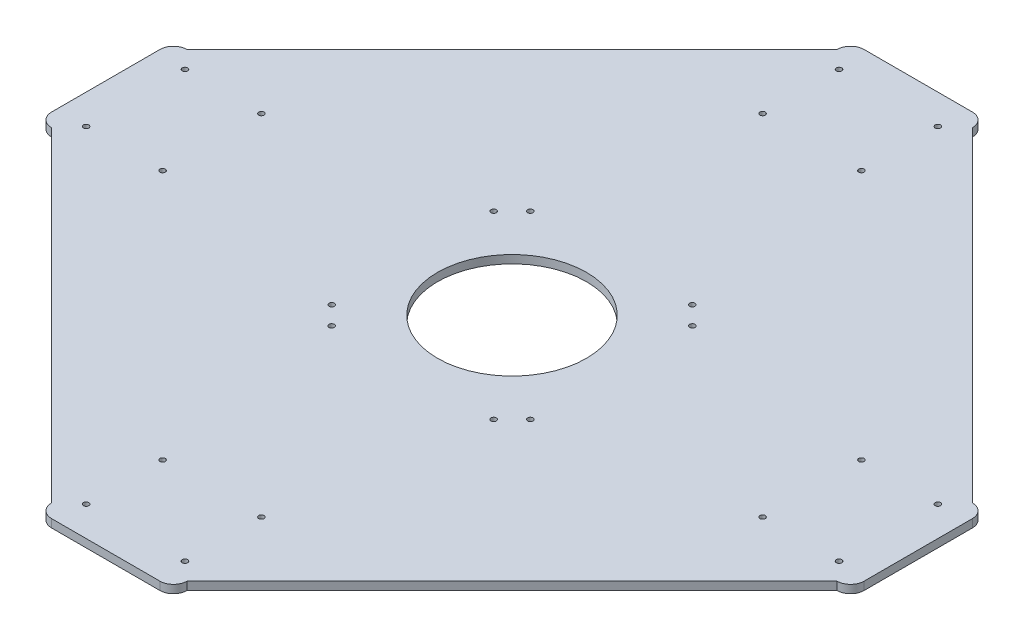
SolidWorks part; units mm, degrees
material "Acrylic (Medium-high impact)"
ref_plane "Front" through (0, 0, 0) normal (0, 0, 1) x (1, 0, 0)
ref_plane "Top" through (0, 0, 0) normal (0, 1, 0) x (1, 0, 0)
ref_plane "Right" through (0, 0, 0) normal (1, 0, 0) x (0, 0, -1)
sketch "Sketch1" plane through (0, 0, 0) normal (0, 1, 0) x (1, 0, 0)
  line L0 (-110, 50) -> (-300, 50)
  line L1 (280, -50) -> (90, -50)
  line L2 (290, -40) -> (290, 40)
  line L3 (280, 50) -> (90, 50)
  line L4 (-310, -40) -> (-310, 40)
  line L5 (-60, 100) -> (-110, 50)
  line L6 (90, 50) -> (40, 100)
  line L7 (30, -300) -> (-50, -300)
  line L8 (40, -290) -> (40, -100)
  line L9 (30, 300) -> (-50, 300)
  line L10 (-60, -290) -> (-60, -100)
  line L11 (90, -50) -> (40, -100)
  line L12 (-60, -100) -> (-110, -50)
  line L16 (-110, -50) -> (-300, -50)
  line L18 (40, 100) -> (40, 290)
  line L19 (-60, 100) -> (-60, 290)
  arc A0 (-50, 300) -> (-60, 290) centre (-50, 290) ccw
  arc A1 (40, 290) -> (30, 300) centre (30, 290) ccw
  arc A2 (290, 40) -> (280, 50) centre (280, 40) ccw
  arc A3 (280, -50) -> (290, -40) centre (280, -40) ccw
  arc A4 (30, -300) -> (40, -290) centre (30, -290) ccw
  arc A5 (-50, -300) -> (-60, -290) centre (-50, -290) cw
  arc A6 (-300, -50) -> (-310, -40) centre (-300, -40) cw
  arc A7 (-300, 50) -> (-310, 40) centre (-300, 40) ccw
  point P0 (0, 0)
  point P1 (8.4315, 46.1032)
  point P2 (128.4315, 46.1032)
  point P3 (8.4315, -56.5685)
  point P4 (128.4315, -56.5685)
  point P5 (0, 0)
  point P10 (0, 0)
  point P15 (-60, -50)
  point P17 (-60, 50)
  point P18 (-56.5685, -56.5685)
  point P23 (56.5685, 56.5685)
  point P25 (40, -50)
  point P28 (40, 50)
  point P31 (-60, 300)
  point P34 (40, 300)
  point P37 (290, 50)
  point P43 (40, -300)
  point P48 (-310, -50)
  point P51 (-310, 50)
  dimension "D1" = 600
  dimension "D5" = 10
  dimension "D2" = 100
  dimension "D3" = 100
  dimension "D4" = 600
  dimension "D6" = 190
  dimension "D7" = 190
  dimension "D8" = 190
  dimension "D9" = 190
extrude "Boss-Extrude1" add sketch "Sketch1" along normal blind 6
sketch "Sketch4" plane through (0, 6, 0) normal (0, 1, 0) x (1, 0, 0)
  line L0 (-10, 300) -> (-10, -432.1332) construction
  line L1 (30, 300) -> (-50, 300) construction
  line L2 (-338.2481, 0) -> (378.576, 0) construction
  circle A0 centre (-10, 0) radius 0.4957
extrude "Cut-Extrude3" cut sketch "Sketch4" against normal blind 10
sketch "Sketch5" plane through (0, 6, 0) normal (0, 1, 0) x (1, 0, 0)
  line L0 (-300, 50) -> (-60, 290)
  line L1 (-250, 50) -> (-60, 240)
  line L2 (-110, 50) -> (-300, 50) construction
  line L3 (-60, 100) -> (-60, 290) construction
  line L4 (-60, 240) -> (-60, 290)
  line L5 (-250, 50) -> (-300, 50)
  line L6 (40, 290) -> (280, 50)
  line L7 (280, 50) -> (230, 50)
  line L8 (230, 50) -> (40, 240)
  line L9 (40, 240) -> (40, 290)
  line L10 (280, -50) -> (40, -290)
  line L11 (40, -290) -> (40, -240)
  line L12 (40, -240) -> (230, -49.078)
  line L13 (230, -49.078) -> (280, -50)
  line L14 (-300, -50) -> (-60, -290)
  line L15 (-60, -290) -> (-60, -240)
  line L16 (-60, -240) -> (-250, -50)
  line L17 (-250, -50) -> (-300, -50)
  point P25 (-10, 2)
  dimension "D1" = 50
  dimension "D2" = 50
  dimension "D3" = 50
  dimension "D4" = 50
  dimension "D5" = 50
  dimension "D6" = 50
  dimension "D7" = 50
  dimension "D8" = 50
extrude "Boss-Extrude3" add sketch "Sketch5" against normal blind 6
sketch "Sketch6" plane through (0, 6, 0) normal (0, 1, 0) x (1, 0, 0)
  circle A0 centre (-37.8241, 287.837) radius 2
  circle A1 centre (-37.8241, 272.837) radius 2
  circle A4 centre (-46.4831, 221.5369) radius 2
  circle A5 centre (-46.4831, 135.0679) radius 2
  circle A6 centre (-69.8176, 73.3345) radius 2
  circle A7 centre (49.8176, 73.3345) radius 2
  circle A8 centre (26.4831, 135.0679) radius 2
  circle A9 centre (26.4831, 221.5369) radius 2
  circle A10 centre (191.3604, 113.6396) radius 2
  circle A11 centre (128.6396, 176.3604) radius 2
  circle A12 centre (17.8241, 272.837) radius 2
  circle A13 centre (17.8241, 287.837) radius 2
  circle A14 centre (-10, 0) radius 4
  dimension "D1" = 4
  dimension "D2" = 4
  dimension "D4" = 8
  dimension "D8" = 4
  dimension "D9" = 4
  dimension "D10" = 4
  dimension "D3" = 15
extrude "Cut-Extrude4" cut sketch "Sketch6" against normal blind 12
pattern_circular "CirPattern1" count 4 over 360 about axis through (-10, 0, 0) along (0, 1, 0) of "Cut-Extrude4"
sketch "Sketch7" plane through (0, 6, 0) normal (0, 1, 0) x (1, 0, 0)
  line L0 (40, 240) -> (230, 50) construction
  line L1 (40, 100) -> (40, 240) construction
  line L2 (90, 50) -> (40, 100) construction
  line L3 (230, 50) -> (90, 50) construction
  line L4 (90, -50) -> (229.0824, -50) construction
  line L5 (229.0824, -50) -> (40, -240) construction
  line L6 (40, -100) -> (90, -50) construction
  line L7 (40, -240) -> (40, -100) construction
  line L8 (-60, 240) -> (-60, 100) construction
  line L9 (-250, 50) -> (-60, 240) construction
  line L10 (-60, 100) -> (-110, 50) construction
  line L11 (-110, 50) -> (-250, 50) construction
  line L12 (-110, -50) -> (-60, -100) construction
  line L13 (-250, -50) -> (-110, -50) construction
  line L14 (-60, -240) -> (-250, -50) construction
  line L15 (-60, -100) -> (-60, -240) construction
  line L16 (40, 240) -> (230, 50)
  line L17 (40, 100) -> (40, 240)
  line L18 (90, 50) -> (40, 100)
  line L19 (230, 50) -> (90, 50)
  line L20 (90, -50) -> (229.0824, -50)
  line L21 (229.0824, -50) -> (40, -240)
  line L22 (40, -100) -> (90, -50)
  line L23 (40, -240) -> (40, -100)
  line L24 (-60, 240) -> (-60, 100)
  line L25 (-250, 50) -> (-60, 240)
  line L26 (-60, 100) -> (-110, 50)
  line L27 (-110, 50) -> (-250, 50)
  line L28 (-110, -50) -> (-60, -100)
  line L29 (-250, -50) -> (-110, -50)
  line L30 (-60, -240) -> (-250, -50)
  line L31 (-60, -100) -> (-60, -240)
extrude "Boss-Extrude4" add sketch "Sketch7" against normal up to surface (6 mm away) up to face at (63.3345, 0, -57.8176)
sketch "Sketch8" plane through (0, 0, 0) normal (0, -1, 0) x (-1, 0, 0)
  circle A0 centre (-279, 20) radius 2.5
  circle A1 centre (-279, -20) radius 2.5
extrude "Cut-Extrude5" [suppressed] cut sketch "Sketch8" against normal blind 144
pattern_circular "CirPattern2" [suppressed] count 4 over 360
sketch "Sketch9" plane through (0, 0, 0) normal (0, -1, 0) x (-1, 0, 0)
  circle A0 centre (-255, -20) radius 2.5
  circle A1 centre (-255, 20) radius 2.5
extrude "Cut-Extrude6" [suppressed] cut sketch "Sketch9" against normal blind 144
pattern_circular "CirPattern3" [suppressed] count 4 over 360
sketch "Sketch10" plane through (0, 6, 0) normal (0, 1, 0) x (1, 0, 0)
  line L0 (-310, 40) -> (-310, -40) construction
  line L1 (-50, -300) -> (30, -300) construction
  point P0 (-57, 33)
  point P1 (37, 33)
  point P2 (-57, -33)
  point P3 (37, -33)
  dimension "D1" = 94
  dimension "D2" = 66
  dimension "D3" = 253
  dimension "D4" = 267
ref_plane "Plane1" through (-10, 0, 0) normal (1, 0, 0) x (0, 0, -1)
ref_plane "Plane2" through (0, 0, 0) normal (0, 0, 1) x (1, 0, 0)
ref_plane "Plane3" through (-10, 0, 0) normal (-1, 0, 0) x (0, 0, 1)
sketch "Sketch11" plane through (0, 6, 0) normal (0, 1, 0) x (1, 0, 0)
  point P0 (32.7129, 23.7813)
  point P1 (-226.182, -59.3281)
  point P3 (-30.4306, -32.5)
  point P4 (31.3831, -32.5)
  point P6 (-29.1008, 23.7813)
hole_wizard "Ø4.0mm Dowel Hole5" positions "Sketch16" profile "Sketch17" hole size "Ø4.0" standard "ANSI Metric"
sketch "Sketch16" plane through (0, 6, 0) normal (0, 1, 0) x (1, 0, 0)
  point P0 (-29.1008, 23.7813)
  point P3 (32.7129, 23.7813)
  point P6 (31.3831, -32.5)
  point P9 (-30.4306, -32.5)
sketch "Sketch17" plane through (-29.1008, 6, -23.7813) normal (1, 0, 0) x (0, 0, 1)
  line L0 (0, 0) -> (0, 26.6017)
  line L1 (0, 26.6017) -> (2, 25.4)
  line L2 (2, 25.4) -> (2, 0)
  line L5 (2, 0) -> (0, 0)
  line L10 (0, 26.6017) -> (-2, 25.4) construction
  line L11 (0, -6.35) -> (0, 107.95) construction
  dimension "Hole Dia." = 4
  dimension "Hole Depth" = 25.4
  dimension "Drill Angle" = 118
sketch "Sketch23" plane through (0, 0, 0) normal (0, -1, 0) x (1, 0, 0)
  point P0 (-10, -24.0416)
  point P1 (-34.0416, 0)
  point P2 (-10, 24.0416)
  point P3 (14.0416, 0)
hole_wizard "Ø4.0mm Dowel Hole3" [suppressed] positions "Sketch26" profile "Sketch27" hole size "Ø4.0" standard "ANSI Metric"
sketch "Sketch26" plane through (0, 4, 0) normal (0, 1, 0) x (1, 0, 0)
  point P0 (-10, 24.0416)
  point P2 (-34.0416, 0)
  point P4 (14.0416, 0)
  point P6 (-10, -24.0416)
sketch "Sketch27" plane through (-10, 4, -24.0416) normal (1, 0, 0) x (0, 0, 1)
  line L0 (0, 0) -> (0, 99.5117)
  line L1 (0, 99.5117) -> (2, 98.31)
  line L2 (2, 98.31) -> (2, 0)
  line L5 (2, 0) -> (0, 0)
  line L10 (0, 99.5117) -> (-2, 98.31) construction
  line L11 (0, -6.35) -> (0, 107.95) construction
  dimension "Hole Dia." = 4
  dimension "Hole Depth" = 98.31
  dimension "Drill Angle" = 118
ref_plane "Plane4" through (-10, 0, 0) normal (-1, 0, 0) x (0, 0, 1)
sketch "Sketch28" plane through (0, 0, 0) normal (0, -1, 0) x (1, 0, 0)
  point P0 (-288, 36.4831)
  point P1 (-288, -36.4831)
  point P2 (-46.4831, -278)
  point P3 (26.4831, -278)
  point P4 (268, -36.4831)
  point P5 (268, 36.4831)
  point P6 (-46.4831, 278)
  point P7 (26.4831, 278)
hole_wizard "Ø4.0mm Dowel Hole4" positions "Sketch29" profile "Sketch30" hole size "Ø4.0" standard "ANSI Metric"
sketch "Sketch29" plane through (0, 0, 0) normal (0, -1, 0) x (-1, 0, 0)
  point P0 (46.4831, -278)
  point P3 (-26.4831, -278)
  point P6 (-268, -36.4831)
  point P9 (-268, 36.4831)
  point P12 (-26.4831, 278)
  point P15 (46.4831, 278)
  point P18 (288, 36.4831)
  point P21 (288, -36.4831)
sketch "Sketch30" plane through (-46.4831, 0, 278) normal (1, 0, 0) x (0, 0, -1)
  line L0 (0, 0) -> (0, 99.5117)
  line L1 (0, 99.5117) -> (2, 98.31)
  line L2 (2, 98.31) -> (2, 0)
  line L5 (2, 0) -> (0, 0)
  line L10 (0, 99.5117) -> (-2, 98.31) construction
  line L11 (0, -6.35) -> (0, 107.95) construction
  dimension "Hole Dia." = 4
  dimension "Hole Depth" = 98.31
  dimension "Drill Angle" = 118
ref_plane "Plane5" through (-10, 0, 0) normal (1, 0, 0) x (0, 0, -1)
sketch "Sketch31" plane through (0, 0, 0) normal (0, -1, 0) x (1, 0, 0)
  circle A0 centre (-10, 0) radius 55
  dimension "D1" = 110
extrude "Cut-Extrude7" cut sketch "Sketch31" against normal blind 22
sketch "Sketch32" plane through (0, 0, 0) normal (0, -1, 0) x (1, 0, 0)
  circle A0 centre (-148.6396, 176.3604) radius 3.8372
  circle A1 centre (-211.3604, 113.6396) radius 3.6912
  circle A2 centre (-282.837, 27.8241) radius 4.0058
  circle A3 centre (-297.837, 27.8241) radius 3.4138
  circle A4 centre (-297.837, -27.8241) radius 2.9463
  circle A5 centre (-282.837, -27.8241) radius 2.6629
  circle A6 centre (-145.0679, -36.4831) radius 3.2103
  circle A7 centre (-145.0679, 36.4574) radius 3.3042
  circle A8 centre (-186.3604, -138.6396) radius 3.4163
  circle A9 centre (-123.8386, -202.7888) radius 5.5768
  circle A10 centre (-37.8241, -272.837) radius 3.3272
  circle A11 centre (-37.8241, -287.837) radius 3.2177
  circle A12 centre (17.8241, -287.837) radius 3.0842
  circle A13 centre (17.8241, -272.837) radius 2.8504
  circle A14 centre (26.4831, -135.0679) radius 3.5817
  circle A15 centre (-46.4831, -135.0679) radius 3.2097
  circle A16 centre (128.6396, -176.3604) radius 5.2236
  circle A17 centre (125.0679, -37.2489) radius 3.24
  circle A18 centre (190.3991, -114.011) radius 6.2176
  circle A19 centre (125.254, 35.6508) radius 3.2815
  circle A20 centre (277.9822, 26.6114) radius 4.0105
  circle A21 centre (262.8622, 26.6114) radius 4.0808
  circle A22 centre (261.8178, -27.8241) radius 4.2907
  circle A23 centre (277.0085, -28.6512) radius 4.0853
  circle A24 centre (25.47, 134.6583) radius 4.4881
  circle A25 centre (-46.1422, 134.0742) radius 4.8991
  circle A26 centre (102.9909, 200.5031) radius 5.4748
  circle A27 centre (165.9468, 137.0679) radius 7.8138
  circle A28 centre (17.4141, 272.2316) radius 3.1876
  circle A29 centre (17.1812, 287.539) radius 2.9298
  circle A30 centre (-38.2931, 286.7977) radius 4.0096
  circle A31 centre (-38.8313, 271.6959) radius 4.0908
  point P80 (0, 0)
extrude "Boss-Extrude5" add sketch "Sketch32" against normal up to vertex (6 mm away)
